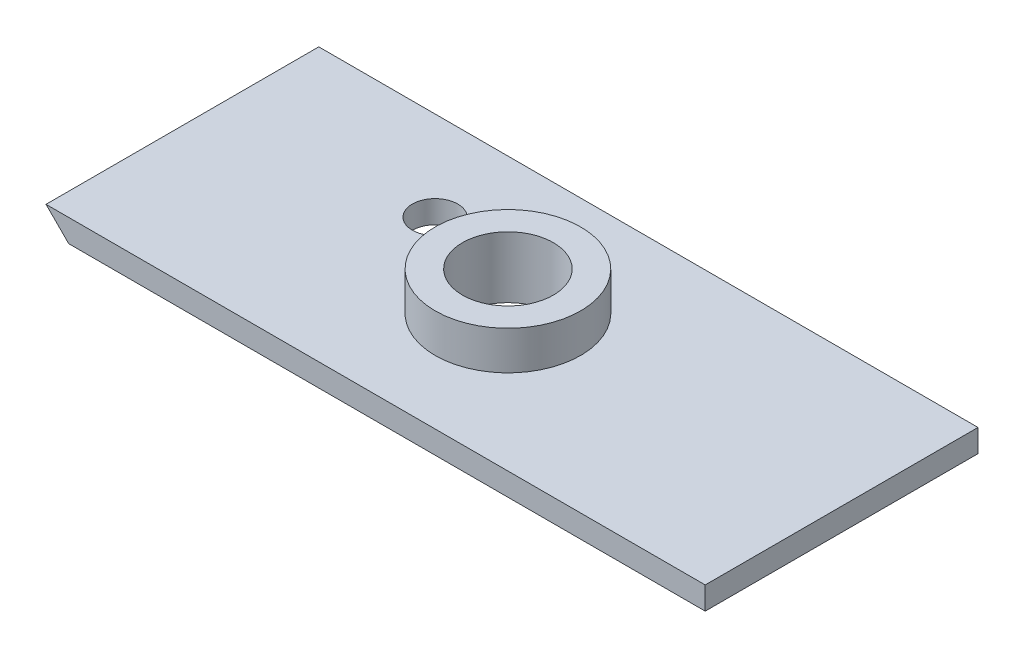
SolidWorks part; units mm, degrees
ref_plane "前视基准面" through (0, 0, 0) normal (0, 0, 1) x (1, 0, 0)
ref_plane "上视基准面" through (0, 0, 0) normal (0, 1, 0) x (1, 0, 0)
ref_plane "右视基准面" through (0, 0, 0) normal (1, 0, 0) x (0, 0, -1)
sketch "草图2" plane through (0, 0, 0) normal (0, 1, 0) x (1, 0, 0)
  line L0 (-21.1496, -1.9474) -> (21.7063, -1.9474) construction
  line L1 (-18.5276, 4.0526) -> (11.4724, 4.0526)
  line L2 (-18.5276, 4.0526) -> (-18.5276, -7.9474)
  line L3 (-18.5276, -7.9474) -> (11.4724, -7.9474)
  line L4 (11.4724, 4.0526) -> (11.4724, -7.9474)
  circle A1 centre (-5.2076, -1.9474) radius 2
  circle A2 centre (-5.2076, -1.9474) radius 3.2 construction
  dimension "D3" = 13.32
  dimension "D4" = 4
  dimension "D5" = 6.4
  dimension "D1" = 30
  dimension "D2" = 12
extrude "凸台-拉伸1" add sketch "草图2" along normal blind 1
sketch "草图3" plane through (0, 1, 0) normal (0, 1, 0) x (1, 0, 0)
  circle A0 centre (-5.2076, -1.9474) radius 2
  circle A1 centre (-5.2076, -1.9474) radius 3.2
extrude "凸台-拉伸2" add sketch "草图3" along normal blind 1.7
sketch "草图4" plane through (0, 0, 0) normal (0, -1, 0) x (1, 0, 0)
  line L0 (-18.5276, -4.0526) -> (-18.5276, 7.9474) construction
  line L6 (11.4724, -4.0526) -> (-18.5276, -4.0526) construction
  circle A0 centre (-10.4812, -0.1227) radius 1
  dimension "D1" = 8.0464
  dimension "D2" = 3.9299
extrude "切除-拉伸1" cut sketch "草图4" against normal blind 5
sketch "草图5" plane through (0, 0, -4.0526) normal (0, 0, -1) x (-1, 0, 0)
  line L0 (18.5276, 1) -> (18.5276, 0)
  line L1 (18.5276, 0) -> (19.5276, 1)
  line L2 (19.5276, 1) -> (18.5276, 1)
  dimension "D1" = 1
extrude "凸台-拉伸3" add sketch "草图5" against normal blind 12
sketch "草图6" plane through (0, 0, 0) normal (0, -1, 0) x (1, 0, 0)
  line L0 (11.4724, -4.0526) -> (-18.5276, -4.0526) construction
  line L1 (11.4724, 7.9474) -> (9.4724, 7.9474)
  line L2 (11.4724, 7.9474) -> (11.4724, -4.0526)
  line L3 (11.4724, -4.0526) -> (9.4724, -4.0526)
  line L4 (9.4724, 7.9474) -> (9.4724, -4.0526)
  dimension "D1" = 2
extrude "切除-拉伸2" cut sketch "草图6" against normal blind 1
sketch "草图7" plane through (0, 0, -4.0526) normal (0, 0, -1) x (-1, 0, 0)
  line L0 (19.5276, 1) -> (18.5276, 0)
  line L1 (18.5276, 0) -> (17.8346, 0)
  line L2 (-9.4724, 0) -> (18.5276, 0) construction
  line L3 (17.8346, 0) -> (18.8346, 1)
  line L4 (-9.4724, 1) -> (19.5276, 1) construction
  line L5 (18.8346, 1) -> (19.5276, 1)
  point P4 (18.8346, 1)
  dimension "D1" = 0.49
